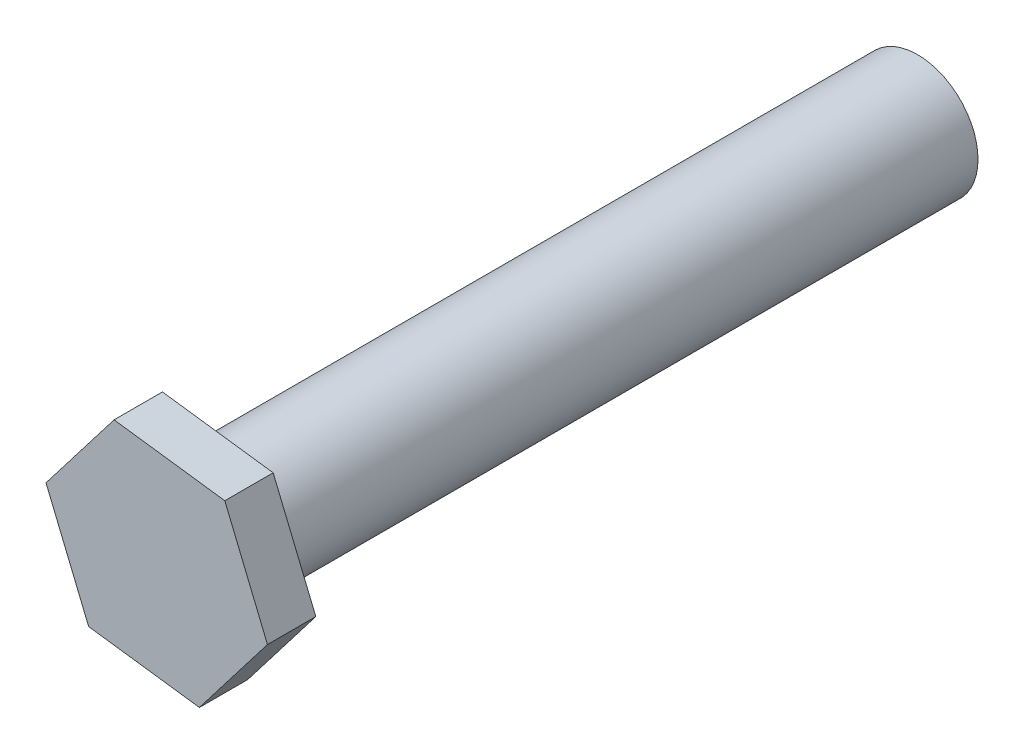
SolidWorks part; units mm, degrees
ref_plane "Front Plane" through (0, 0, 0) normal (0, 0, 1) x (1, 0, 0)
ref_plane "Top Plane" through (0, 0, 0) normal (0, 1, 0) x (1, 0, 0)
ref_plane "Right Plane" through (0, 0, 0) normal (1, 0, 0) x (0, 0, -1)
sketch "Sketch2" plane through (0, 0, 0) normal (0, 0, 1) x (1, 0, 0)
  circle A0 centre (0, 0) radius 25
  dimension "D1" = 50
extrude "Boss-Extrude1" add sketch "Sketch2" along normal blind 260 and the other way blind 34.6
sketch "Sketch3" plane through (0, 0, 260) normal (0, 0, 1) x (1, 0, 0)
  line L1 (28.1481, 36.6199) -> (-17.6397, 42.6869)
  line L2 (-17.6397, 42.6869) -> (-45.7878, 6.067)
  line L3 (-45.7878, 6.067) -> (-28.1481, -36.6199)
  line L4 (-28.1481, -36.6199) -> (17.6397, -42.6869)
  line L5 (17.6397, -42.6869) -> (45.7878, -6.067)
  line L6 (45.7878, -6.067) -> (28.1481, 36.6199)
  circle A0 centre (0, 0) radius 40 construction
  dimension "D1" = 80
extrude "Boss-Extrude2" add sketch "Sketch3" along normal blind 20
